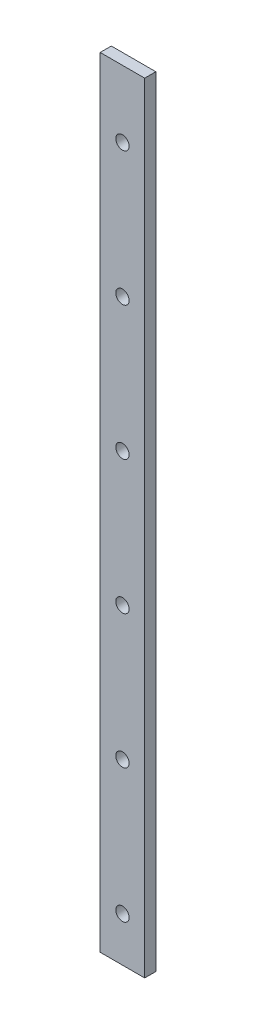
SolidWorks part; units mm, degrees
material "6061 Legierung"
ref_plane "Ebene vorne" through (0, 0, 0) normal (0, 0, 1) x (1, 0, 0)
ref_plane "Ebene oben" through (0, 0, 0) normal (0, 1, 0) x (1, 0, 0)
ref_plane "Ebene rechts" through (0, 0, 0) normal (1, 0, 0) x (0, 0, -1)
sketch "Skizze1" plane through (0, 0, 0) normal (0, 0, 1) x (1, 0, 0)
  line L0 (0, 0) -> (0, 434.3011) construction
  line L2 (-10, 0) -> (10, 0)
  line L3 (-10, 0) -> (-10, 350)
  line L4 (-10, 350) -> (10, 350)
  line L5 (10, 0) -> (10, 350)
  dimension "D1" = 350
  dimension "D2" = 20
extrude "Aufsatz-Linear austragen1" add sketch "Skizze1" along normal blind 5
sketch "Skizze2" plane through (0, 0, 5) normal (0, 0, 1) x (1, 0, 0)
  line L0 (0, 0) -> (0, 64.8533) construction
  line L1 (-10, 0) -> (10, 0) construction
  circle A0 centre (0, 20) radius 3
  dimension "D2" = 6
  dimension "D1" = 20
extrude "Schnitt-Linear austragen1" cut sketch "Skizze2" against normal blind 10
pattern_linear "Lineares Muster1" count 6 spacing 60 along (0, 1, 0) of "Schnitt-Linear austragen1"
